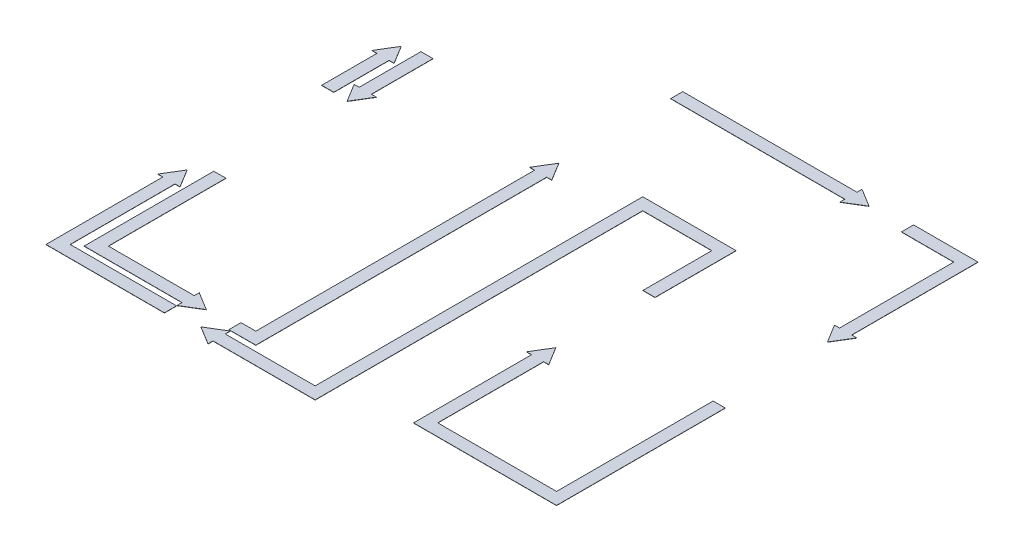
SolidWorks part; units mm, degrees
ref_plane "Front Plane" through (0, 0, 0) normal (0, 0, 1) x (1, 0, 0)
ref_plane "Top Plane" through (0, 0, 0) normal (0, 1, 0) x (1, 0, 0)
ref_plane "Right Plane" through (0, 0, 0) normal (1, 0, 0) x (0, 0, -1)
sketch "Sketch2" plane through (0, 0, 0) normal (0, 1, 0) x (1, 0, 0)
  line L0 (-531.0316, 319.8621) -> (-531.0316, 166.8) construction
  line L1 (-531.0316, -193.7416) -> (-531.0316, -500.1455) construction
  line L2 (-531.0316, -500.1455) -> (-303.197, -500.1455) construction
  line L3 (-187.1624, -500.1455) -> (-135.4907, -500.1455) construction
  line L4 (-135.4907, -500.1455) -> (-135.4907, 206.2244) construction
  line L5 (-135.4907, 543.608) -> (296.4563, 543.608) construction
  line L6 (436.8163, 543.608) -> (581.5022, 543.608) construction
  line L7 (581.5022, 543.608) -> (581.5022, 245.2905) construction
  line L8 (581.5022, -68.1213) -> (581.5022, -471.45) construction
  line L9 (581.5022, -471.45) -> (256.9525, -471.45) construction
  line L10 (256.9525, -471.45) -> (256.9525, -193.7416) construction
  line L11 (256.9525, 82.4088) -> (256.9525, 268.2235) construction
  line L12 (256.9525, 268.2235) -> (55.6141, 268.2235) construction
  line L13 (55.6141, 268.2235) -> (55.6141, -544.0173) construction
  line L14 (55.6141, -544.0173) -> (-182.557, -544.0173) construction
  line L15 (-303.197, -544.0173) -> (-581.8332, -544.0173) construction
  line L16 (-581.8332, -544.0173) -> (-581.8332, -269.1699) construction
  line L17 (-581.8332, 124.5837) -> (-581.8332, 261.6488) construction
  line L18 (-546.0316, 319.8621) -> (-546.0316, 166.8)
  line L19 (-566.8332, 124.5837) -> (-566.8332, 261.6488)
  line L20 (-546.0316, -193.7416) -> (-546.0316, -515.1455)
  line L21 (-546.0316, -515.1455) -> (-303.197, -515.1455)
  line L22 (-303.197, -529.0173) -> (-566.8332, -529.0173)
  line L23 (-566.8332, -529.0173) -> (-566.8332, -269.1699)
  line L24 (-187.1624, -515.1455) -> (-120.4907, -515.1455)
  line L25 (-120.4907, -515.1455) -> (-120.4907, 206.2244)
  line L26 (271.9525, 82.4088) -> (271.9525, 283.2235)
  line L27 (271.9525, 283.2235) -> (40.6141, 283.2235)
  line L28 (40.6141, 283.2235) -> (40.6141, -529.0173)
  line L29 (40.6141, -529.0173) -> (-182.557, -529.0173)
  line L30 (-135.4907, 528.608) -> (296.4563, 528.608)
  line L31 (436.8163, 528.608) -> (566.5022, 528.608)
  line L32 (566.5022, 528.608) -> (566.5022, 245.2905)
  line L33 (566.5022, -68.1213) -> (566.5022, -456.45)
  line L34 (566.5022, -456.45) -> (271.9525, -456.45)
  line L35 (271.9525, -456.45) -> (271.9525, -193.7416)
  line L36 (-516.0316, 319.8621) -> (-516.0316, 166.8)
  line L37 (-596.8332, 124.5837) -> (-596.8332, 261.6488)
  line L38 (-516.0316, -193.7416) -> (-516.0316, -485.1455)
  line L39 (-516.0316, -485.1455) -> (-303.197, -485.1455)
  line L40 (-303.197, -559.0173) -> (-596.8332, -559.0173)
  line L41 (-596.8332, -559.0173) -> (-596.8332, -269.1699)
  line L42 (-187.1624, -485.1455) -> (-150.4907, -485.1455)
  line L43 (-150.4907, -485.1455) -> (-150.4907, 206.2244)
  line L44 (241.9525, 82.4088) -> (241.9525, 253.2235)
  line L45 (241.9525, 253.2235) -> (70.6141, 253.2235)
  line L46 (70.6141, 253.2235) -> (70.6141, -559.0173)
  line L47 (70.6141, -559.0173) -> (-182.557, -559.0173)
  line L48 (-135.4907, 558.608) -> (296.4563, 558.608)
  line L49 (436.8163, 558.608) -> (596.5022, 558.608)
  line L50 (596.5022, 558.608) -> (596.5022, 245.2905)
  line L51 (596.5022, -68.1213) -> (596.5022, -486.45)
  line L52 (596.5022, -486.45) -> (241.9525, -486.45)
  line L53 (241.9525, -486.45) -> (241.9525, -193.7416)
  line L54 (-546.0316, 319.8621) -> (-516.0316, 319.8621)
  line L56 (-566.8332, 124.5837) -> (-596.8332, 124.5837)
  line L58 (-546.0316, -193.7416) -> (-516.0316, -193.7416)
  line L60 (-303.197, -529.0173) -> (-303.197, -559.0173)
  line L62 (-187.1624, -515.1455) -> (-187.1624, -485.1455)
  line L64 (271.9525, 82.4088) -> (241.9525, 82.4088)
  line L66 (-135.4907, 528.608) -> (-135.4907, 558.608)
  line L68 (436.8163, 528.608) -> (436.8163, 558.608)
  line L70 (566.5022, -68.1213) -> (596.5022, -68.1213)
  line L72 (-546.0316, 166.8) -> (-558.5316, 166.8)
  line L73 (-558.5316, 166.8) -> (-531.0316, 121.8)
  line L74 (-531.0316, 121.8) -> (-503.5316, 166.8)
  line L75 (-503.5316, 166.8) -> (-516.0316, 166.8)
  line L76 (-596.8332, 261.6488) -> (-609.3332, 261.6488)
  line L77 (-609.3332, 261.6488) -> (-581.8332, 306.6488)
  line L78 (-581.8332, 306.6488) -> (-554.3332, 261.6488)
  line L79 (-554.3332, 261.6488) -> (-566.8332, 261.6488)
  line L80 (-303.197, -485.1455) -> (-303.197, -472.6455)
  line L81 (-303.197, -472.6455) -> (-258.197, -500.1455)
  line L82 (-258.197, -500.1455) -> (-303.197, -527.6455)
  line L83 (-303.197, -527.6455) -> (-303.197, -515.1455)
  line L84 (-566.8332, -269.1699) -> (-554.3332, -269.1699)
  line L85 (-554.3332, -269.1699) -> (-581.8332, -224.1699)
  line L86 (-581.8332, -224.1699) -> (-609.3332, -269.1699)
  line L87 (-609.3332, -269.1699) -> (-596.8332, -269.1699)
  line L88 (-120.4907, 206.2244) -> (-107.9907, 206.2244)
  line L89 (-107.9907, 206.2244) -> (-135.4907, 251.2244)
  line L90 (-135.4907, 251.2244) -> (-162.9907, 206.2244)
  line L91 (-162.9907, 206.2244) -> (-150.4907, 206.2244)
  line L92 (-182.557, -529.0173) -> (-182.557, -516.5173)
  line L93 (-182.557, -516.5173) -> (-227.557, -544.0173)
  line L94 (-227.557, -544.0173) -> (-182.557, -571.5173)
  line L95 (-182.557, -571.5173) -> (-182.557, -559.0173)
  line L96 (296.4563, 558.608) -> (296.4563, 571.108)
  line L97 (296.4563, 571.108) -> (341.4563, 543.608)
  line L98 (341.4563, 543.608) -> (296.4563, 516.108)
  line L99 (296.4563, 516.108) -> (296.4563, 528.608)
  line L100 (566.5022, 245.2905) -> (554.0022, 245.2905)
  line L101 (554.0022, 245.2905) -> (581.5022, 200.2905)
  line L102 (581.5022, 200.2905) -> (609.0022, 245.2905)
  line L103 (609.0022, 245.2905) -> (596.5022, 245.2905)
  line L104 (241.9525, -193.7416) -> (229.4525, -193.7416)
  line L105 (229.4525, -193.7416) -> (256.9525, -148.7416)
  line L106 (284.4525, -193.7416) -> (271.9525, -193.7416)
  line L107 (256.9525, -148.7416) -> (284.4525, -193.7416)
  dimension "D1" = 55.6141
  dimension "D2" = 256.9525
  dimension "D3" = 296.4563
  dimension "D4" = 436.8163
  dimension "D5" = 581.5022
  dimension "D6" = 135.4907
  dimension "D7" = 182.557
  dimension "D8" = 187.1624
  dimension "D9" = 303.197
  dimension "D10" = 531.0316
  dimension "D11" = 581.8332
  dimension "D12" = 82.4088
  dimension "D13" = 124.5837
  dimension "D14" = 166.8
  dimension "D15" = 206.2244
  dimension "D16" = 245.2905
  dimension "D17" = 261.6488
  dimension "D18" = 268.2235
  dimension "D19" = 319.8621
  dimension "D20" = 543.608
  dimension "D21" = 68.1213
  dimension "D22" = 193.7416
  dimension "D23" = 269.1699
  dimension "D24" = 471.45
  dimension "D25" = 500.1455
  dimension "D26" = 544.0173
  dimension "D29" = 12.5
  dimension "D30" = 12.5
  dimension "D31" = 45
  dimension "D32" = 12.5
  dimension "D33" = 12.5
  dimension "D34" = 45
  dimension "D35" = 12.5
  dimension "D36" = 12.5
  dimension "D37" = 45
  dimension "D38" = 12.5
  dimension "D39" = 12.5
  dimension "D40" = 45
  dimension "D41" = 12.5
  dimension "D42" = 12.5
  dimension "D43" = 45
  dimension "D44" = 12.5
  dimension "D45" = 12.5
  dimension "D46" = 45
  dimension "D47" = 12.5
  dimension "D48" = 12.5
  dimension "D49" = 45
  dimension "D50" = 12.5
  dimension "D51" = 12.5
  dimension "D52" = 45
  dimension "D53" = 12.5
  dimension "D54" = 12.5
  dimension "D55" = 45
  dimension "D27" = 15
  dimension "D28" = 15
extrude "Boss-Extrude2" add sketch "Sketch2" along normal blind 0.5
